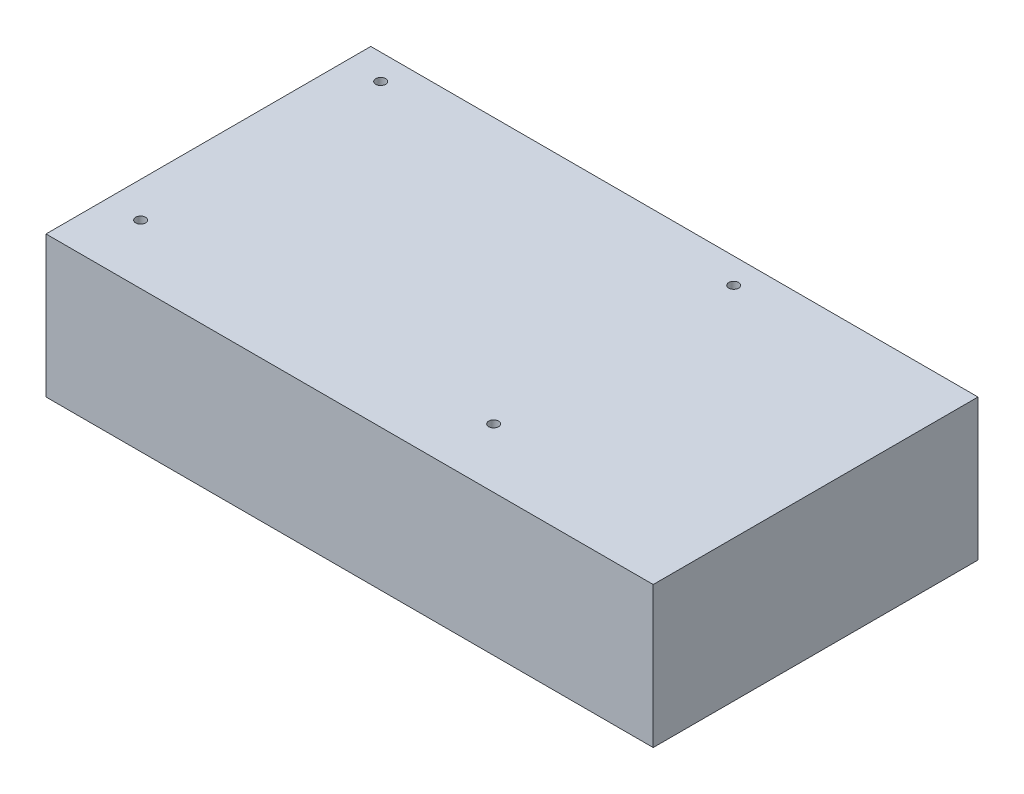
SolidWorks part; units mm, degrees
ref_plane "前视基准面" through (0, 0, 0) normal (0, 0, 1) x (1, 0, 0)
ref_plane "上视基准面" through (0, 0, 0) normal (0, 1, 0) x (1, 0, 0)
ref_plane "右视基准面" through (0, 0, 0) normal (1, 0, 0) x (0, 0, -1)
sketch "草图1" plane through (0, 0, 0) normal (0, 1, 0) x (1, 0, 0)
  line L1 (-56.6865, 50.8135) -> (158.3135, 50.8135)
  line L2 (-56.6865, 50.8135) -> (-56.6865, -64.1865)
  line L3 (-56.6865, -64.1865) -> (158.3135, -64.1865)
  line L4 (158.3135, 50.8135) -> (158.3135, -64.1865)
  line L5 (-56.6865, 50.8135) -> (158.3135, -64.1865) construction
  line L6 (-56.6865, -64.1865) -> (158.3135, 50.8135) construction
  point P4 (50.8135, -6.6865)
  dimension "D1" = 215
  dimension "D2" = 115
extrude "凸台-拉伸1" add sketch "草图1" along normal blind 50
sketch "草图2" plane through (0, 50, 0) normal (0, 1, 0) x (1, 0, 0)
  line L0 (158.3135, -64.1865) -> (158.3135, 50.8135) construction
  line L1 (158.2517, 32.6012) -> (32.2517, 32.6012)
  line L2 (158.2517, 32.6012) -> (158.2517, -52.3988)
  line L3 (158.2517, -52.3988) -> (32.2517, -52.3988)
  line L4 (32.2517, 32.6012) -> (32.2517, -52.3988)
  line L5 (158.2517, 32.6012) -> (32.2517, -52.3988) construction
  line L6 (158.2517, -52.3988) -> (32.2517, 32.6012) construction
  point P4 (95.2517, -9.8988)
  dimension "D1" = 126
  dimension "D2" = 85
  dimension "D3" = 0.0619
sketch "草图3" plane through (0, 50, 0) normal (0, 1, 0) x (1, 0, 0)
  line L0 (-56.6865, 50.8135) -> (-56.6865, -64.1865) construction
  line L1 (-44.1865, 41.8135) -> (80.8135, 41.8135) construction
  line L2 (-44.1865, 41.8135) -> (-44.1865, -43.1865) construction
  line L3 (-44.1865, -43.1865) -> (80.8135, -43.1865) construction
  line L4 (80.8135, 41.8135) -> (80.8135, -43.1865) construction
  line L5 (-44.1865, 41.8135) -> (80.8135, -43.1865) construction
  line L6 (-44.1865, -43.1865) -> (80.8135, 41.8135) construction
  line L7 (158.3135, 50.8135) -> (-56.6865, 50.8135) construction
  circle A0 centre (-44.1865, 41.8135) radius 1.75
  circle A1 centre (-44.1865, -43.1865) radius 1.75
  circle A2 centre (80.8135, -43.1865) radius 1.75
  circle A3 centre (80.8135, 41.8135) radius 1.75
  point P4 (18.3135, -0.6865)
  dimension "D5" = 3.5
  dimension "D1" = 125
  dimension "D2" = 85
  dimension "D3" = 12.5
  dimension "D4" = 9
extrude "切除-拉伸1" cut sketch "草图3" against normal blind 5
